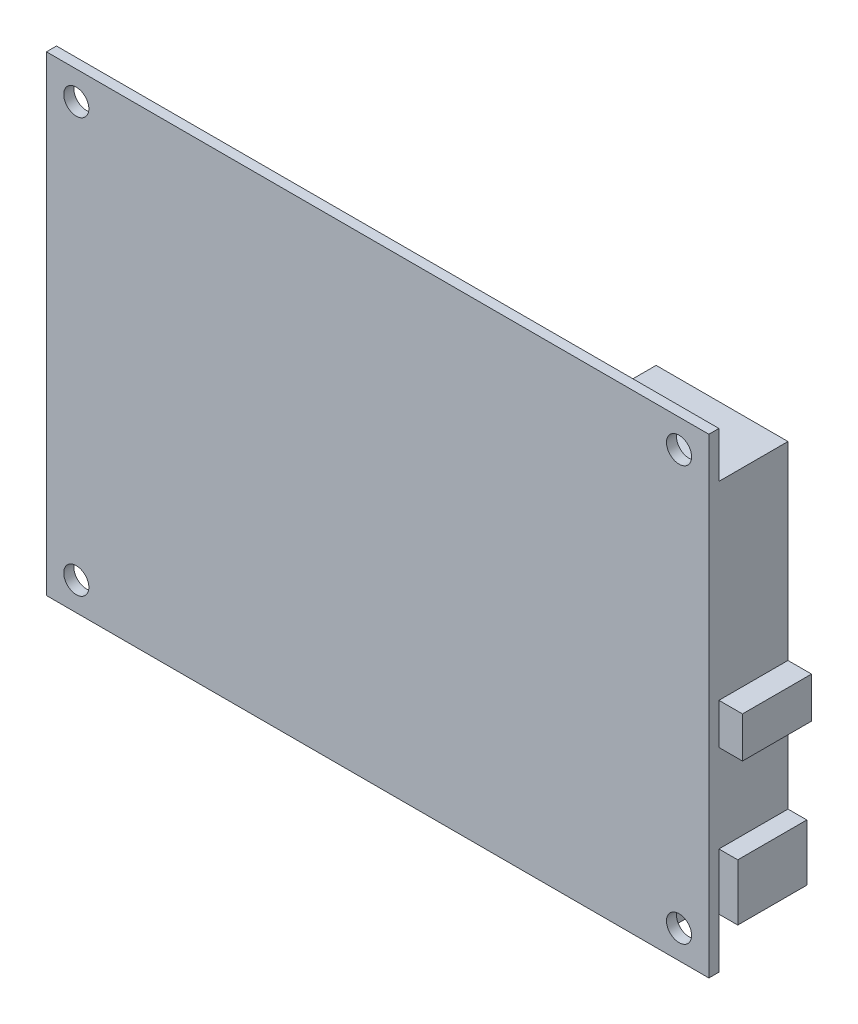
SolidWorks part; units mm, degrees
ref_plane "Plan de face" through (0, 0, 0) normal (0, 0, 1) x (1, 0, 0)
ref_plane "Plan de dessus" through (0, 0, 0) normal (0, 1, 0) x (1, 0, 0)
ref_plane "Plan de droite" through (0, 0, 0) normal (1, 0, 0) x (0, 0, -1)
sketch "Esquisse1" plane through (0, 0, 0) normal (0, 0, 1) x (1, 0, 0)
  line L0 (-48, 33) -> (48, -33) construction
  line L1 (-52.75, 37.5) -> (52.75, 37.5)
  line L2 (-52.75, 37.5) -> (-52.75, -37.5)
  line L3 (-52.75, -37.5) -> (52.75, -37.5)
  line L4 (52.75, 37.5) -> (52.75, -37.5)
  line L5 (0, 37.5) -> (0, -37.5) construction
  circle A0 centre (-48, 33) radius 2
  circle A1 centre (48, 33) radius 2
  circle A2 centre (-48, -33) radius 2
  circle A3 centre (48, -33) radius 2
  point P14 (0, 0)
  point P15 (0, 0)
  dimension "D4" = 4
  dimension "D1" = 105.5
  dimension "D2" = 75
  dimension "D3" = 96
  dimension "D5" = 66
extrude "Boss.-Extru.1" add sketch "Esquisse1" along normal blind 1.6
sketch "Esquisse5" plane through (0, 0, 0) normal (0, 0, -1) x (-1, 0, 0)
  line L10 (-52.75, 30.2) -> (-31.75, 30.2)
  line L11 (-52.75, -37.5) -> (-52.75, 37.5) construction
  line L12 (-31.75, 30.2) -> (-31.75, -29.5)
  line L13 (-31.75, -29.5) -> (-55.75, -29.5)
  line L14 (-55.75, -29.5) -> (-55.75, -20.5)
  line L15 (-55.75, -20.5) -> (-52.75, -20.5)
  line L16 (-52.75, -20.5) -> (-52.75, -6.5)
  line L17 (-52.75, -6.5) -> (-56.5, -6.5)
  line L18 (-56.5, -6.5) -> (-56.5, 0)
  line L19 (-56.5, 0) -> (-52.75, 0)
  line L20 (-52.75, 0) -> (-52.75, 30.2)
  line L21 (-52.75, 37.5) -> (52.75, 37.5) construction
  line L22 (52.75, -37.5) -> (-52.75, -37.5) construction
  dimension "D1" = 7.3
  dimension "D2" = 21
  dimension "D3" = 3
  dimension "D4" = 8
  dimension "D5" = 9
  dimension "D6" = 31
  dimension "D7" = 3.75
  dimension "D8" = 6.5
extrude "Boss.-Extru.2" add sketch "Esquisse5" along normal blind 11
sketch "Esquisse6" plane through (0, 0, 0) normal (0, 0, -1) x (-1, 0, 0)
  line L0 (52.75, -37.5) -> (-52.75, -37.5) construction
  line L1 (-29.55, -37.5) -> (-42.75, -37.5)
  line L2 (-29.55, -37.5) -> (-29.55, -29.5)
  line L3 (-29.55, -29.5) -> (-42.75, -29.5)
  line L4 (-42.75, -37.5) -> (-42.75, -29.5)
  line L5 (-52.75, -29.5) -> (-31.75, -29.5) construction
  line L6 (-52.75, -37.5) -> (-52.75, -29.5) construction
  dimension "D1" = 10
  dimension "D2" = 13.2
extrude "Boss.-Extru.3" add sketch "Esquisse6" along normal blind 16
sketch "Esquisse7" plane through (0, 0, 0) normal (0, 0, -1) x (-1, 0, 0)
  line L0 (52.75, -37.5) -> (-29.55, -37.5) construction
  line L1 (-26.95, -37.5) -> (44.05, -37.5)
  line L2 (-26.95, -37.5) -> (-26.95, -33.65)
  line L3 (-26.95, -33.65) -> (44.05, -33.65)
  line L4 (44.05, -37.5) -> (44.05, -33.65)
  line L5 (52.75, 37.5) -> (52.75, -37.5) construction
  dimension "D1" = 8.7
  dimension "D2" = 3.85
  dimension "D3" = 71
extrude "Boss.-Extru.4" add sketch "Esquisse7" along normal blind 6.15
sketch "Esquisse8" plane through (0, 0, 0) normal (0, 0, -1) x (-1, 0, 0)
  line L0 (-52.75, 37.5) -> (52.75, 37.5) construction
  line L1 (-12.45, 23.67) -> (35.55, 23.67)
  line L2 (-12.45, 23.67) -> (-12.45, 21.17)
  line L3 (-12.45, 21.17) -> (35.55, 21.17)
  line L4 (35.55, 23.67) -> (35.55, 21.17)
  line L5 (-3.45, -24.6167) -> (35.55, -24.6167)
  line L6 (-3.45, -24.6167) -> (-3.45, -28)
  line L7 (-3.45, -28) -> (35.55, -28)
  line L8 (35.55, -24.6167) -> (35.55, -28)
  line L9 (52.75, -37.5) -> (44.05, -37.5) construction
  line L10 (52.75, 37.5) -> (52.75, -37.5) construction
  dimension "D1" = 48
  dimension "D2" = 2.5
  dimension "D3" = 39
  dimension "D4" = 13.83
  dimension "D5" = 9.5
  dimension "D6" = 17.2
extrude "Boss.-Extru.5" add sketch "Esquisse8" along normal blind 8.8
sketch "Esquisse9" plane through (0, 0, 0) normal (0, 0, -1) x (-1, 0, 0)
  line L0 (52.75, -37.5) -> (44.05, -37.5) construction
  line L1 (48, 2.25) -> (53.75, 2.25)
  line L2 (48, 2.25) -> (48, -5.5)
  line L3 (48, -5.5) -> (53.75, -5.5)
  line L4 (53.75, 2.25) -> (53.75, -5.5)
  line L5 (52.75, 37.5) -> (52.75, -37.5) construction
  dimension "D1" = 32
  dimension "D2" = 7.75
  dimension "D3" = 5.75
  dimension "D4" = 1
extrude "Boss.-Extru.6" add sketch "Esquisse9" along normal blind 3
